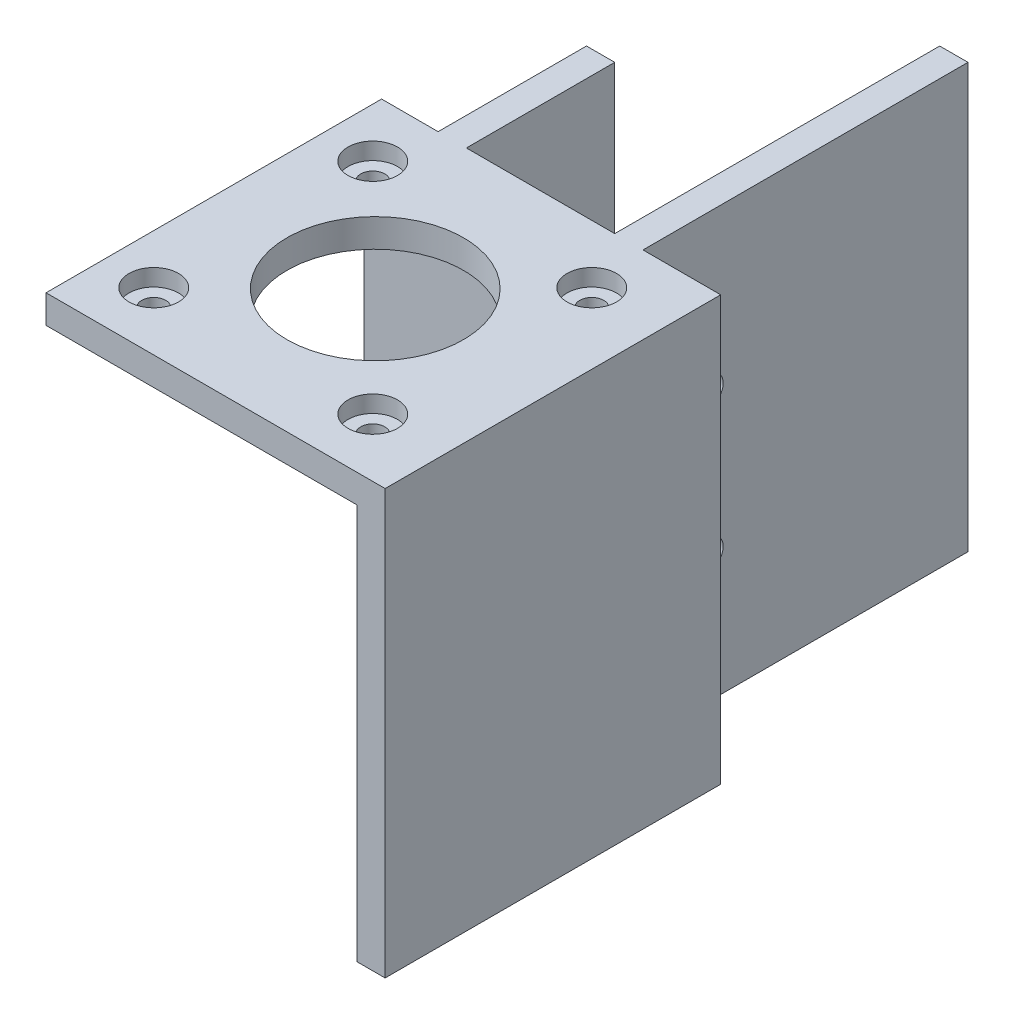
SolidWorks part; units mm, degrees
ref_plane "Front Plane" through (0, 0, 0) normal (0, 0, 1) x (1, 0, 0)
ref_plane "Top Plane" through (0, 0, 0) normal (0, 1, 0) x (1, 0, 0)
ref_plane "Right Plane" through (0, 0, 0) normal (1, 0, 0) x (0, 0, -1)
sketch "Sketch1" plane through (0, 0, 0) normal (0, 0, 1) x (1, 0, 0)
  line L1 (-26.5244, 60) -> (18.4756, 60)
  line L2 (-26.5244, 60) -> (-26.5244, 0)
  line L3 (-26.5244, 0) -> (18.4756, 0)
  line L4 (18.4756, 60) -> (18.4756, 0)
  dimension "D1" = 45
  dimension "D2" = 60
extrude "Boss-Extrude1" add sketch "Sketch1" against normal blind 23.5
sketch "Sketch2" plane through (0, 0, 0) normal (0, 0, 1) x (1, 0, 0)
  line L0 (18.4756, 0) -> (18.4756, 60) construction
  line L1 (-26.5244, 60) -> (18.4756, 60)
  line L2 (-26.5244, 60) -> (-26.5244, 56)
  line L3 (-26.5244, 56) -> (18.4756, 56)
  line L4 (18.4756, 60) -> (18.4756, 56)
  line L5 (-26.5244, 60) -> (-26.5244, 0) construction
  line L6 (18.4756, 60) -> (-26.5244, 60) construction
  dimension "D1" = 4
extrude "Boss-Extrude2" add sketch "Sketch2" along normal blind 45
sketch "Sketch4" plane through (0, 0, 0) normal (0, -1, 0) x (1, 0, 0)
  line L0 (-26.5244, -23.5) -> (18.4756, -23.5) construction
  line L1 (-14.5244, -2.5) -> (6.4756, -2.5)
  line L2 (-14.5244, -2.5) -> (-14.5244, -23.5)
  line L3 (-14.5244, -23.5) -> (6.4756, -23.5)
  line L4 (6.4756, -2.5) -> (6.4756, -23.5)
  line L5 (-26.5244, -23.5) -> (-26.5244, 0) construction
  line L6 (-14.5244, -13) -> (-26.5244, -13) construction
  line L7 (6.4756, -13) -> (18.4756, -13) construction
  line L8 (18.4756, -23.5) -> (18.4756, 0) construction
  point P15 (-14.5244, -13)
  dimension "D1" = 21
  dimension "D2" = 21
extrude "Cut-Extrude1" cut sketch "Sketch4" against normal through all
sketch "Sketch5" plane through (0, 60, 0) normal (0, 1, 0) x (1, 0, 0)
  line L0 (-3.7244, 0) -> (-3.7244, -45) construction
  line L1 (-26.2244, 0) -> (18.7756, 0) construction
  line L2 (-26.5244, 23.5) -> (-26.5244, -45) construction
  line L5 (-3.7244, -21.2) -> (-26.5244, -21.2) construction
  circle A0 centre (-3.7244, -21.2) radius 12.5
  point P5 (-3.7244, 0)
  dimension "D2" = 25
  dimension "D1" = 21.2
  dimension "D3" = 22.8
extrude "Cut-Extrude2" cut sketch "Sketch5" against normal up to next
sketch "Sketch6" plane through (-26.5244, 0, 0) normal (-1, 0, 0) x (0, 0, 1)
  line L0 (0, 56) -> (0, 0) construction
  line L1 (0, 28) -> (-23.5, 28) construction
  line L2 (-23.5, 60) -> (-23.5, 0) construction
  line L3 (-23.5, 0) -> (0, 0) construction
  line L4 (-11.75, 0) -> (-11.75, 60) construction
  line L5 (-23.5, 60) -> (45, 60) construction
  point P1 (0, 28)
  point P14 (-11.75, 38)
  point P16 (-11.75, 18)
  dimension "D1" = 10
sketch "Sketch9" plane through (18.4756, 0, 0) normal (1, 0, 0) x (0, 0, -1)
  line L6 (0, 56) -> (0, 0)
  line L7 (0, 0) -> (23.5, 0)
  line L8 (23.5, 0) -> (23.5, 60)
  line L9 (23.5, 60) -> (-45, 60)
  line L10 (-45, 60) -> (-45, 56)
  line L11 (-45, 56) -> (0, 56)
  line L12 (0, 56) -> (0, 0)
  line L13 (0, 0) -> (23.5, 0)
  line L14 (23.5, 0) -> (23.5, 60)
  line L15 (23.5, 60) -> (-45, 60)
  line L16 (-45, 60) -> (-45, 56)
  line L17 (-45, 56) -> (0, 56)
  point P2 (11.75, 38)
  point P4 (11.75, 18)
  dimension "D1" = 0
sketch "Sketch11" plane through (0, 60, 0) normal (0, 1, 0) x (1, 0, 0)
  line L0 (-4.0244, -45) -> (-4.0244, 2.5) construction
  line L1 (18.4756, -45) -> (-26.5244, -45) construction
  line L2 (6.4756, 2.5) -> (-14.5244, 2.5) construction
  line L3 (-4.0244, -21.25) -> (18.4898, -21.25) construction
  point P8 (11.4756, -36.75)
  point P11 (11.4756, -5.75)
  point P12 (-19.5244, -5.75)
  point P13 (-19.5244, -36.75)
  dimension "D1" = 15.5
  dimension "D2" = 15.5
sketch "Sketch13" plane through (18.4756, 0, 0) normal (1, 0, 0) x (0, 0, -1)
  line L0 (2.5, 60) -> (2.5, 0) construction
  line L1 (2.5, 60) -> (2.5, 0)
  line L3 (2.5, 0) -> (23.5, 0)
  line L4 (2.5, 0) -> (2.5, 60)
  line L5 (2.5, 60) -> (23.5, 60)
  line L6 (0, 56) -> (0, 0)
  line L7 (0, 0) -> (23.5, 0)
  line L8 (23.5, 0) -> (23.5, 60)
  line L9 (23.5, 60) -> (-45, 60)
  line L10 (-45, 60) -> (-45, 56)
  line L11 (-45, 56) -> (0, 56)
  line L12 (0, 56) -> (0, 0)
  line L13 (0, 0) -> (23.5, 0)
  line L14 (23.5, 0) -> (23.5, 60)
  line L15 (23.5, 60) -> (-45, 60)
  line L16 (-45, 60) -> (-45, 56)
  line L17 (-45, 56) -> (0, 56)
  line L18 (23.5, 0) -> (23.5, 60)
  dimension "D1" = 0
extrude "Cut-Extrude3" cut sketch "Sketch13" against normal blind 8 contours L4 L3 L18 L5
sketch "Sketch14" plane through (-26.5244, 0, 0) normal (-1, 0, 0) x (0, 0, 1)
  line L0 (-2.5, 60) -> (-2.5, 0) construction
  line L1 (-2.5, 60) -> (-2.5, 0)
  line L3 (-2.5, 60) -> (-23.5, 60)
  line L4 (-2.5, 60) -> (-2.5, 0)
  line L5 (-2.5, 0) -> (-23.5, 0)
  line L6 (0, 0) -> (0, 56)
  line L7 (0, 56) -> (45, 56)
  line L8 (45, 56) -> (45, 60)
  line L9 (45, 60) -> (-23.5, 60)
  line L10 (-23.5, 60) -> (-23.5, 0)
  line L11 (-23.5, 0) -> (0, 0)
  line L12 (0, 0) -> (0, 56)
  line L13 (0, 56) -> (45, 56)
  line L14 (45, 56) -> (45, 60)
  line L15 (45, 60) -> (-23.5, 60)
  line L16 (-23.5, 60) -> (-23.5, 0)
  line L17 (-23.5, 0) -> (0, 0)
  line L18 (-23.5, 60) -> (-23.5, 0)
  dimension "D1" = 0
extrude "Cut-Extrude4" cut sketch "Sketch14" against normal blind 8
sketch "Sketch15" plane through (10.4756, 0, 0) normal (1, 0, 0) x (0, 0, -1)
  line L4 (23.5, 60) -> (2.5, 60)
  line L5 (2.5, 60) -> (2.5, 0)
  line L6 (2.5, 0) -> (23.5, 0)
  line L7 (23.5, 0) -> (23.5, 60)
  line L8 (23.5, 60) -> (2.5, 60)
  line L9 (2.5, 60) -> (2.5, 0)
  line L10 (2.5, 0) -> (23.5, 0)
  line L11 (23.5, 0) -> (23.5, 60)
  point P2 (11.75, 18)
  point P4 (11.75, 38)
  dimension "D1" = 0
sketch "Sketch16" plane through (-18.5244, 0, 0) normal (-1, 0, 0) x (0, 0, 1)
  line L0 (0, 28) -> (-23.5, 28) construction
  line L1 (0, 28) -> (-23.5, 28) construction
  line L4 (-2.5, 0) -> (-2.5, 60)
  line L5 (-2.5, 60) -> (-23.5, 60)
  line L6 (-23.5, 60) -> (-23.5, 0)
  line L7 (-23.5, 0) -> (-2.5, 0)
  line L8 (-2.5, 0) -> (-2.5, 60)
  line L9 (-2.5, 60) -> (-23.5, 60)
  line L10 (-23.5, 60) -> (-23.5, 0)
  line L11 (-23.5, 0) -> (-2.5, 0)
  circle A0 centre (-11.75, 38) radius 2.1
  circle A1 centre (-11.75, 18) radius 2.1
  point P2 (-11.75, 18)
  point P4 (-11.75, 38)
  dimension "D2" = 2.1
  dimension "D1" = 0
sketch "Sketch22" plane through (0, 0, -23.5) normal (0, 0, -1) x (-1, 0, 0)
  line L1 (-6.4756, 60) -> (-10.4756, 60)
  line L2 (-6.4756, 60) -> (-6.4756, 0)
  line L3 (-6.4756, 0) -> (-10.4756, 0)
  line L4 (-10.4756, 60) -> (-10.4756, 0)
extrude "Boss-Extrude6" add sketch "Sketch22" along normal blind 25
hole_wizard "CBORE for M3 Pan Head Machine Screw1" positions "3DSketch7" profile "Sketch19" counterbore size "M3" standard "ANSI Metric" end condition up to next
sketch3d "3DSketch7"
  point P0 (-42.9375, 0, 35.2557)
  point P2 (11.4756, 60, 36.75)
  point P5 (-19.5244, 60, 36.75)
  point P8 (11.4756, 60, 5.75)
  point P11 (-19.5244, 60, 5.75)
sketch "Sketch19" plane through (-19.5244, 60, 5.75) normal (1, 0, 0) x (0, 0, 1)
  line L0 (0, 0) -> (0, 4.001)
  line L1 (0, 4.001) -> (1.7, 4.001)
  line L3 (1.7, 4.001) -> (1.7, 2.4)
  line L4 (1.7, 2.4) -> (3.5, 2.4)
  line L5 (3.5, 2.4) -> (3.5, 0)
  line L7 (3.5, 0) -> (0, 0)
  line L11 (0, -6.35) -> (0, 107.95) construction
  dimension "Thru Hole Dia." = 3.4
  dimension "Thru Hole Depth" = 4.001
  dimension "C'Bore Dia." = 7
  dimension "C'Bore Depth" = 2.4
extrude "Cut-Extrude5" cut sketch "Sketch16" against normal through all contours A0 | A1
sketch "Sketch21" plane through (18.4756, 0, 0) normal (1, 0, 0) x (0, 0, -1)
  line L1 (-45, 60) -> (2.5, 60)
  line L2 (-45, 60) -> (-45, 0)
  line L3 (-45, 0) -> (2.5, 0)
  line L4 (2.5, 60) -> (2.5, 0)
extrude "Boss-Extrude5" add sketch "Sketch21" along normal blind 3 and the other way blind 1
equation "\"2..50cm\"=1"
